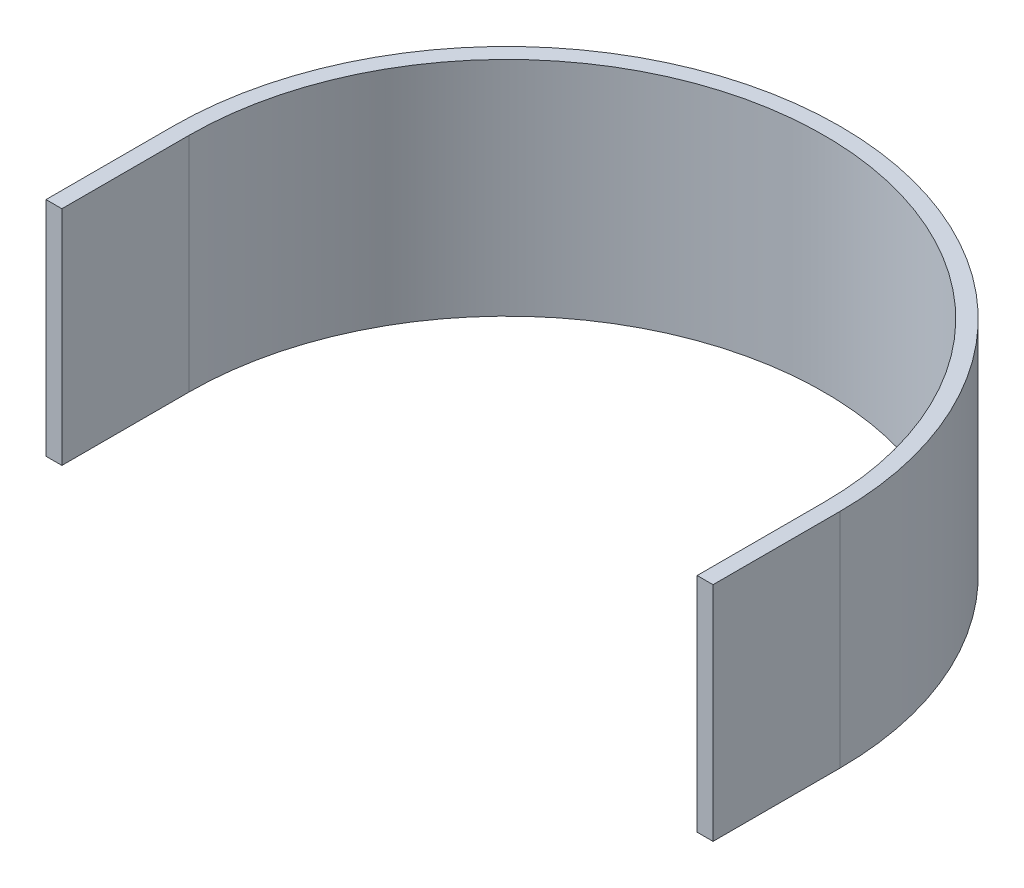
SolidWorks part; units mm, degrees
material "PE High Density"
ref_plane "Front Plane" through (0, 0, 0) normal (0, 0, 1) x (1, 0, 0)
ref_plane "Top Plane" through (0, 0, 0) normal (0, 1, 0) x (1, 0, 0)
ref_plane "Right Plane" through (0, 0, 0) normal (1, 0, 0) x (0, 0, -1)
sketch "Sketch1" plane through (0, 0, 0) normal (0, 1, 0) x (1, 0, 0)
  line L0 (-63.5, 0) -> (-63.5, -25.4)
  line L1 (-63.5, -25.4) -> (-66.675, -25.4)
  line L2 (-66.675, -25.4) -> (-66.675, 0)
  line L3 (0, 63.5) -> (0, -63.5) construction
  line L4 (63.5, -25.4) -> (66.675, -25.4)
  line L5 (63.5, 0) -> (63.5, -25.4)
  line L6 (66.675, -25.4) -> (66.675, 0)
  circle A0 centre (0, 0) radius 63.5 construction
  arc A1 (-63.5, 0) -> (63.5, 0) centre (0, 0) cw
  arc A2 (-66.675, 0) -> (66.675, 0) centre (0, 0) cw
  dimension "D1" = 127
  dimension "D2" = 25.4
  dimension "D3" = 3.175
extrude "Boss-Extrude1" add sketch "Sketch1" along normal blind 44.45 contours A2 L2 L1 L0 A1 L5 L4 L6
